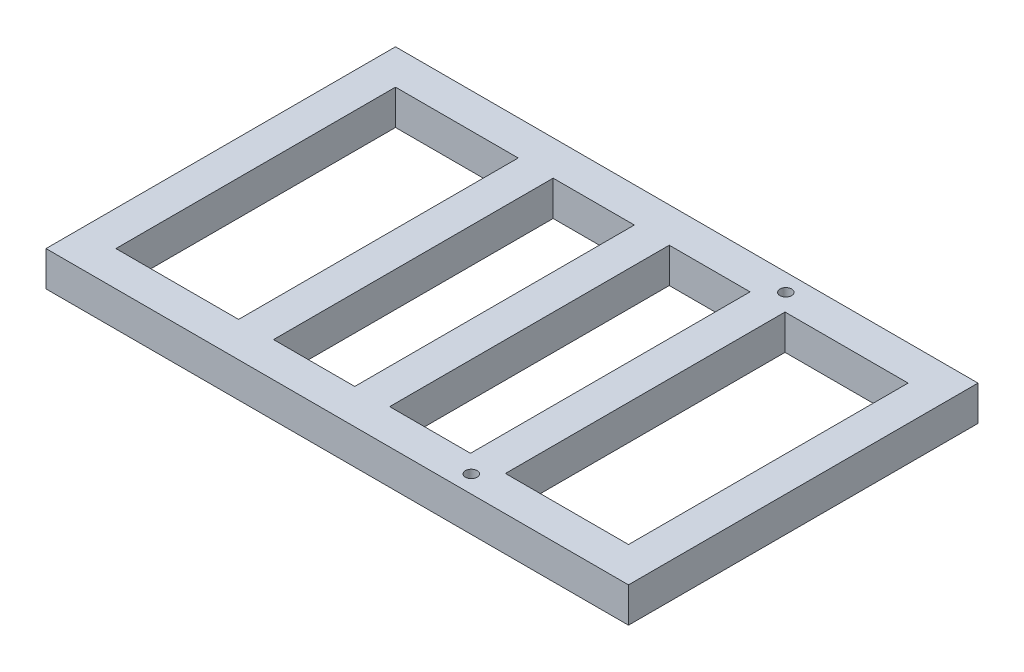
SolidWorks part; units mm, degrees
ref_plane "Front Plane" through (0, 0, 0) normal (0, 0, 1) x (1, 0, 0)
ref_plane "Top Plane" through (0, 0, 0) normal (0, 1, 0) x (1, 0, 0)
ref_plane "Right Plane" through (0, 0, 0) normal (1, 0, 0) x (0, 0, -1)
sketch "Sketch2" plane through (0, 0, 0) normal (0, 1, 0) x (1, 0, 0)
  line L0 (-55, 0) -> (55, 0) construction
  line L1 (-220, 120) -> (220, 120)
  line L2 (-220, 120) -> (-220, -120)
  line L3 (-220, -120) -> (220, -120)
  line L4 (220, 120) -> (220, -120)
  line L5 (-220, 120) -> (220, -120) construction
  line L6 (-220, -120) -> (220, 120) construction
  line L7 (0, -55) -> (0, 55) construction
  line L9 (-250, 150) -> (250, 150)
  line L10 (-250, 150) -> (-250, -150)
  line L11 (-250, -150) -> (250, -150)
  line L12 (250, 150) -> (250, -150)
  line L13 (-250, 150) -> (250, -150) construction
  line L14 (-250, -150) -> (250, 150) construction
  point P0 (0, 0)
  point P9 (0, 0)
  dimension "D1" = 30
  dimension "D2" = 30
  dimension "D3" = 30
  dimension "D4" = 30
  dimension "D5" = 500
  dimension "D6" = 300
extrude "Boss-Extrude1" add sketch "Sketch2" along normal blind 30
sketch "Sketch3" plane through (0, 30, 0) normal (0, 1, 0) x (1, 0, 0)
  line L0 (0, -16.5) -> (0, 16.5) construction
  line L1 (-15, 120) -> (15, 120)
  line L2 (-15, 120) -> (-15, -120)
  line L3 (-15, -120) -> (15, -120)
  line L4 (15, 120) -> (15, -120)
  line L5 (-15, 120) -> (15, -120) construction
  line L6 (-15, -120) -> (15, 120) construction
  line L7 (-16.5, 0) -> (16.5, 0) construction
  line L8 (-220, -120) -> (220, -120) construction
  point P0 (0, 0)
  dimension "D1" = 30
extrude "Boss-Extrude2" add sketch "Sketch3" against normal up to vertex (30 mm away)
sketch "Sketch4" plane through (0, 30, 0) normal (0, 1, 0) x (1, 0, 0)
  line L0 (-16.5, 0) -> (16.5, 0) construction
  line L1 (-114.681, -120) -> (-84.681, -120)
  line L2 (-114.681, -120) -> (-114.681, 120)
  line L3 (-114.681, 120) -> (-84.681, 120)
  line L4 (-84.681, -120) -> (-84.681, 120)
  line L5 (-114.681, -120) -> (-84.681, 120) construction
  line L6 (-114.681, 120) -> (-84.681, -120) construction
  line L7 (-15, 120) -> (-220, 120) construction
  line L8 (220, 120) -> (15, 120) construction
  line L9 (84.3653, -120) -> (114.3653, -120)
  line L10 (84.3653, -120) -> (84.3653, 120)
  line L11 (84.3653, 120) -> (114.3653, 120)
  line L12 (114.3653, -120) -> (114.3653, 120)
  line L13 (84.3653, -120) -> (114.3653, 120) construction
  line L14 (84.3653, 120) -> (114.3653, -120) construction
  point P0 (-99.681, 0)
  point P9 (99.3653, 0)
  dimension "D1" = 30
  dimension "D2" = 30
sketch "Sketch7" plane through (0, 0, 0) normal (0, 1, 0) x (1, 0, 0)
extrude "Boss-Extrude3" add sketch "Sketch4" against normal up to vertex (30 mm away)
sketch "Sketch8" plane through (0, 30, 0) normal (0, 1, 0) x (1, 0, 0)
  line L2 (250, 150) -> (-250, 150) construction
  circle A1 centre (100.0184, 135) radius 5
  dimension "D1" = 10
  dimension "D2" = 15
extrude "Cut-Extrude1" cut sketch "Sketch8" against normal blind 32
sketch "Sketch9" plane through (0, 30, 0) normal (0, 1, 0) x (1, 0, 0)
  line L0 (-250, -150) -> (250, -150) construction
  circle A0 centre (100.0604, -135) radius 5
  dimension "D1" = 10
  dimension "D2" = 15
extrude "Cut-Extrude2" cut sketch "Sketch9" against normal blind 34
